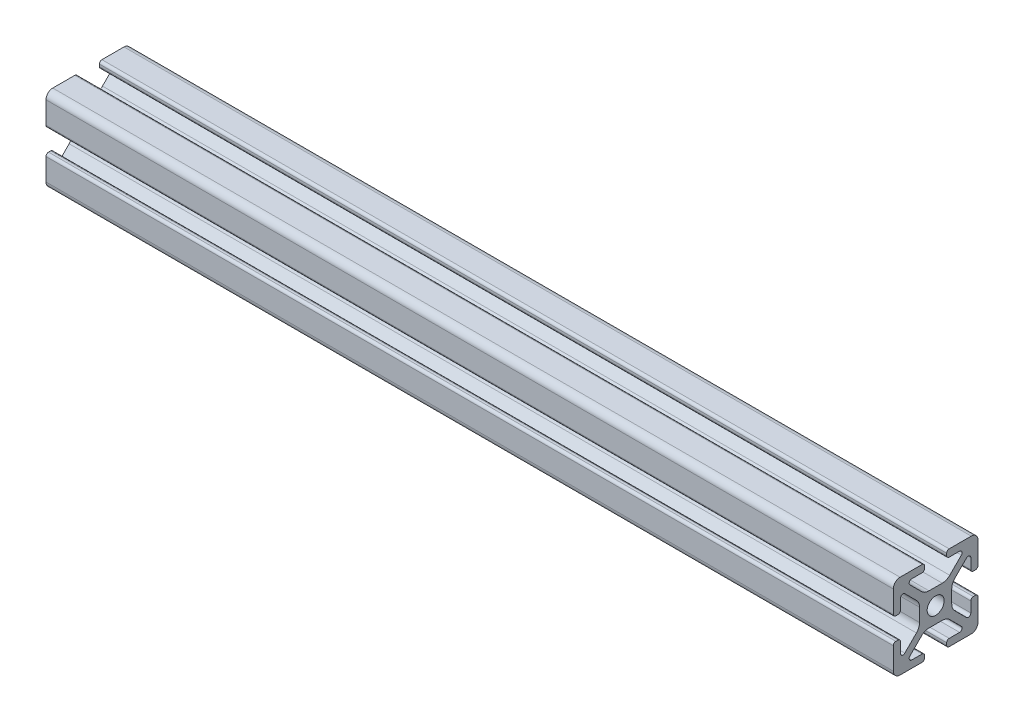
SolidWorks part; units mm, degrees
ref_plane "Front Plane" through (0, 0, 0) normal (0, 0, 1) x (1, 0, 0)
ref_plane "Top Plane" through (0, 0, 0) normal (0, 1, 0) x (1, 0, 0)
ref_plane "Right Plane" through (0, 0, 0) normal (1, 0, 0) x (0, 0, -1)
sketch "Sketch1" plane through (0, 0, 0) normal (1, 0, 0) x (0, 0, -1)
  line L0 (0, -12.7) -> (0, 12.7) construction
  line L1 (-7.874, 12.7) -> (7.874, 12.7) construction
  line L2 (-12.7, 0) -> (12.7, 0) construction
  line L3 (-7.874, 12.7) -> (-7.874, 4.826) construction
  line L4 (-3.302, 12.7) -> (3.302, 12.7) construction
  line L5 (-12.7, -12.7) -> (12.7, -12.7) construction
  line L6 (-12.7, 12.7) -> (12.7, 12.7) construction
  circle A0 centre (0, 0) radius 2.54 construction
  point P7 (0, 12.7)
  point P10 (0, 0)
  point P13 (0, 0)
  point P16 (0, 12.7)
  point P17 (-3.302, 12.7)
  point P18 (3.302, 12.7)
  point P21 (0, -12.7)
  point P24 (0, 12.7)
  dimension "Center Hole Diameter" = 5.08
  dimension "Rail Width" = 25.4
  dimension "Rail Height" = 25.4
  dimension "T-Slot Depth" = 7.874
  dimension "D1" = 15.748
  dimension "T-Slot Width" = 6.604
  dimension "D2" = 12.7
sketch "Sketch2" plane through (0, 0, 0) normal (0, 0, 1) x (1, 0, 0)
  line L0 (-127, 0) -> (127, 0) construction
  line L1 (0, 0) -> (0, 26.104) construction
  line L2 (127, -12.7) -> (127, 12.7) construction
  line L3 (-127, -12.7) -> (-127, 12.7) construction
  point P3 (-88.9, 0)
  point P8 (0, 0)
  point P9 (88.9, 0)
  point P12 (127, 0)
  point P15 (-127, 0)
  dimension "Length" = 254
  dimension "D1" = 38.1
  dimension "D2" = 25.4
sketch "Sketch3" plane through (0, 0, 0) normal (1, 0, 0) x (0, 0, -1)
  line L0 (0, 4.826) -> (1.9842, 4.826)
  line L1 (0, -12.7) -> (0, 12.7) construction
  line L2 (4.2293, 5.7559) -> (7.7135, 9.2402)
  line L6 (7.1747, 10.541) -> (4.064, 10.541)
  line L7 (3.302, 11.303) -> (3.302, 11.938)
  line L8 (-7.874, 12.7) -> (7.874, 12.7) construction
  line L10 (0, 0) -> (12.7, 12.7) construction
  line L13 (0, 4.826) -> (0, 2.54)
  line L14 (4.826, 0) -> (2.54, 0)
  line L31 (4.826, 0) -> (4.826, 1.9842)
  line L32 (4.064, 12.7) -> (10.668, 12.7)
  line L33 (-12.7, 0) -> (12.7, 0) construction
  line L34 (-12.7, 12.7) -> (12.7, 12.7) construction
  line L35 (5.7559, 4.2293) -> (9.2402, 7.7135)
  line L36 (0, 12.7) -> (12.7, 12.7) construction
  line L37 (12.7, 12.7) -> (12.7, 8.0234) construction
  line L38 (11.303, 3.302) -> (11.938, 3.302)
  line L39 (10.541, 7.1747) -> (10.541, 4.064)
  line L40 (12.7, 10.668) -> (12.7, 4.064)
  arc A0 (2.54, 0) -> (0, 2.54) centre (0, 0) ccw
  arc A1 (1.9842, 4.826) -> (4.2293, 5.7559) centre (1.9842, 8.001) ccw
  circle A2 centre (0, 0) radius 2.54 construction
  arc A7 (3.302, 11.938) -> (4.064, 12.7) centre (4.064, 11.938) cw
  arc A8 (4.064, 10.541) -> (3.302, 11.303) centre (4.064, 11.303) cw
  arc A14 (4.826, 1.9842) -> (5.7559, 4.2293) centre (8.001, 1.9842) cw
  arc A16 (10.668, 12.7) -> (12.7, 10.668) centre (10.668, 10.668) cw
  arc A17 (7.1747, 10.541) -> (7.7135, 9.2402) centre (7.1747, 9.779) cw
  arc A18 (10.541, 7.1747) -> (9.2402, 7.7135) centre (9.779, 7.1747) ccw
  arc A19 (10.541, 4.064) -> (11.303, 3.302) centre (11.303, 4.064) ccw
  arc A20 (11.938, 3.302) -> (12.7, 4.064) centre (11.938, 4.064) ccw
  point P37 (3.2994, 4.826)
  point P49 (12.7, 3.302)
  point P52 (3.302, 12.7)
  point P55 (3.302, 10.541)
  dimension "D4" = 3.175
  dimension "D9" = 2.159
  dimension "D12" = 0.762
  dimension "D3" = 2.032
  dimension "D8" = 0.762
  dimension "D2" = 45
  dimension "D5" = 0
  dimension "D6" = 45
  dimension "D7" = 2.159
extrude "Boss-Extrude1" add sketch "Sketch3" against normal up to vertex (127 mm away) and the other way up to vertex (127 mm away) up to point (-127, 0, 0) other way up to point (127, 0, 0)
mirror "Mirror1" about plane through (0, 0, 0) normal (0, 1, 0) of bodies 104
mirror "Mirror2" about plane through (0, 0, 0) normal (0, 0, 1) of bodies 105
equation "\"D1@Sketch2\"=\"Rail Height@Sketch1\"*1.5"
equation "\"D2@Sketch2\"=\"Rail Height@Sketch1\""
